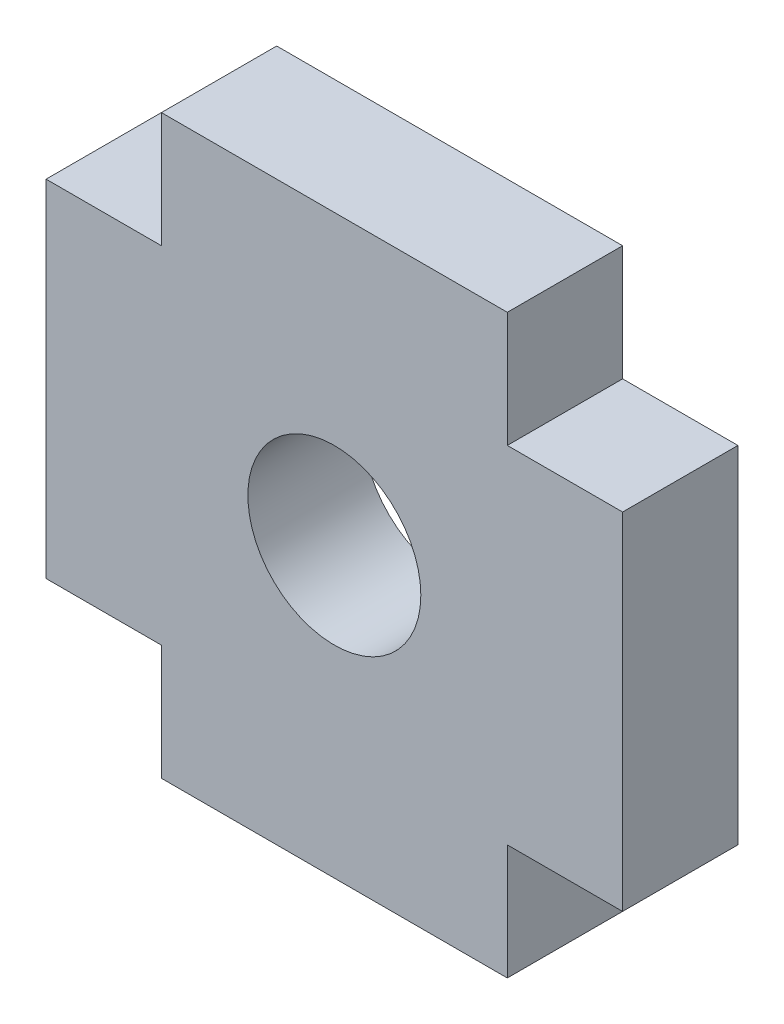
SolidWorks part; units mm, degrees
material "Acrylic (Medium-high impact)"
ref_plane "Front Plane" through (0, 0, 0) normal (0, 0, 1) x (1, 0, 0)
ref_plane "Top Plane" through (0, 0, 0) normal (0, 1, 0) x (1, 0, 0)
ref_plane "Right Plane" through (0, 0, 0) normal (1, 0, 0) x (0, 0, -1)
sketch "Model" plane through (0, 0, 0) normal (0, 0, 1) x (1, 0, 0)
  line L235 (2078.676, 1290.2235) -> (2080.676, 1290.2235)
  line L236 (2080.676, 1290.2235) -> (2080.676, 1288.2235)
  line L237 (2080.676, 1288.2235) -> (2086.676, 1288.2235)
  line L238 (2086.676, 1288.2235) -> (2086.676, 1290.2235)
  line L239 (2086.676, 1296.2235) -> (2086.676, 1298.2235)
  line L240 (2086.676, 1298.2235) -> (2080.676, 1298.2235)
  line L241 (2080.676, 1298.2235) -> (2080.676, 1296.2235)
  line L242 (2080.676, 1296.2235) -> (2078.676, 1296.2235)
  line L243 (2078.676, 1296.2235) -> (2078.676, 1290.2235)
  line L244 (2086.676, 1296.2235) -> (2088.676, 1296.2235)
  line L245 (2088.676, 1296.2235) -> (2088.676, 1290.2235)
  line L246 (2088.676, 1290.2235) -> (2086.676, 1290.2235)
  circle A75 centre (2083.676, 1293.2235) radius 1.5
extrude "Boss-Extrude1" add sketch "Model" along normal blind 2
